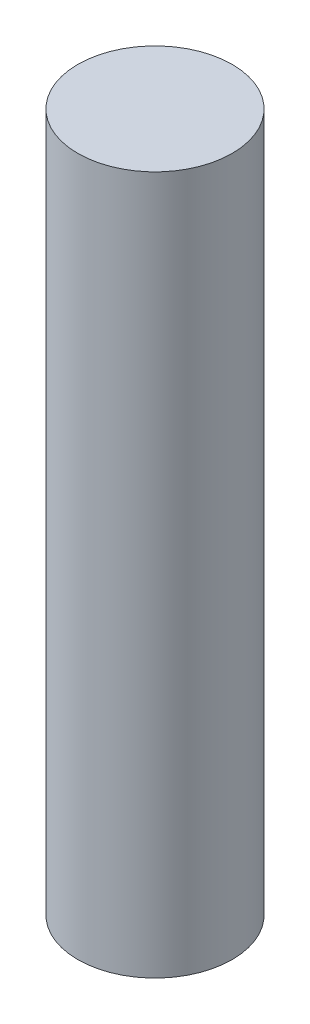
SolidWorks part; units mm, degrees
ref_plane "Ön Düzlem" through (0, 0, 0) normal (0, 0, 1) x (1, 0, 0)
ref_plane "Üst Düzlem" through (0, 0, 0) normal (0, 1, 0) x (1, 0, 0)
ref_plane "Sağ Düzlem" through (0, 0, 0) normal (1, 0, 0) x (0, 0, -1)
sketch "Çizim1" plane through (0, 0, 0) normal (0, 1, 0) x (1, 0, 0)
  circle A0 centre (0, 0) radius 20
  dimension "D1" = 40
extrude "Yükseklik-Ekstrüzyon1" add sketch "Çizim1" along normal blind 181
